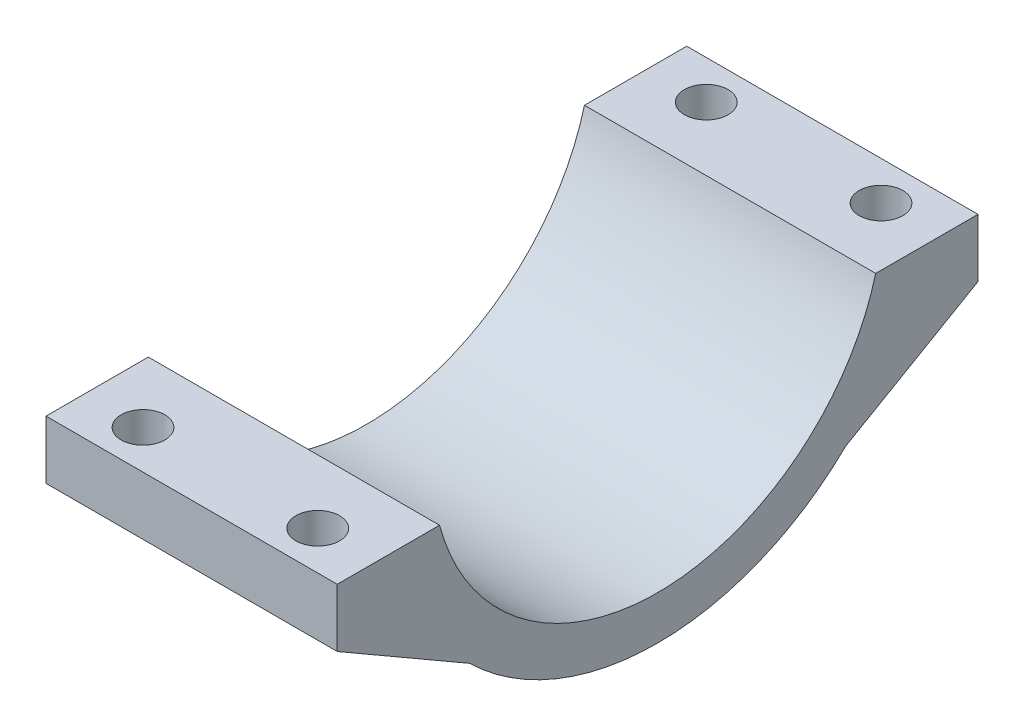
SolidWorks part; units mm, degrees
ref_plane "前视基准面" through (0, 0, 0) normal (0, 0, 1) x (1, 0, 0)
ref_plane "上视基准面" through (0, 0, 0) normal (0, 1, 0) x (1, 0, 0)
ref_plane "右视基准面" through (0, 0, 0) normal (1, 0, 0) x (0, 0, -1)
sketch "草图1" plane through (0, 0, 0) normal (1, 0, 0) x (0, 0, -1)
  line L0 (0, 0) -> (0, -4) construction
  line L1 (-22, -4) -> (-14.975, -4) construction
  line L2 (0, -4) -> (14.975, -4) construction
  line L3 (-22, -4) -> (-14.975, -4)
  line L4 (-22, -4) -> (-22, -8)
  line L5 (-22, -8) -> (-16.6808, -8)
  line L6 (22, -4) -> (22, -8)
  line L7 (14.975, -4) -> (22, -4) construction
  line L8 (0, -4) -> (14.975, -4) construction
  line L9 (14.975, -4) -> (22, -4)
  line L10 (-13.2759, -8) -> (13.2759, -8) construction
  line L11 (16.6808, -8) -> (22, -8)
  line L12 (13.2759, -8) -> (16.6808, -8) construction
  line L13 (-16.6808, -8) -> (-13.2759, -8) construction
  line L14 (-14.975, -4) -> (0, -4) construction
  line L15 (-14.975, -4) -> (0, -4) construction
  arc A0 (-14.975, -4) -> (14.975, -4) centre (0, 0) ccw
  arc A1 (-16.6808, -8) -> (16.6808, -8) centre (0, 0) ccw
  arc A2 (18.0624, -4) -> (-18.0624, -4) centre (0, 0) ccw construction
  arc A3 (14.975, -4) -> (-14.975, -4) centre (0, 0) ccw construction
  arc A4 (-18.0624, -4) -> (-16.6808, -8) centre (0, 0) ccw construction
  arc A5 (16.6808, -8) -> (18.0624, -4) centre (0, 0) ccw construction
  point P7 (0, -4)
  dimension "D1" = 31
  dimension "D4" = 37
  dimension "D2" = 44
  dimension "D3" = 4
  dimension "D5" = 4
extrude "凸台-拉伸1" add sketch "草图1" along normal blind 20
sketch "草图2" plane through (0, -8, 0) normal (0, -1, 0) x (1, 0, 0)
  line L0 (10, 22) -> (10, 16.6808) construction
  line L1 (20, 22) -> (0, 22) construction
  line L2 (20, 16.6808) -> (0, 16.6808) construction
  line L3 (0, 19.3404) -> (10, 19.3404) construction
  line L4 (0, 22) -> (0, 16.6808) construction
  circle A1 centre (4, 19.3404) radius 1.5
  circle A2 centre (16, 19.3404) radius 1.5
  dimension "D1" = 3
  dimension "D2" = 12
sketch "草图3" plane through (0, 0, 0) normal (-1, 0, 0) x (0, 0, 1)
  line L0 (22, -8) -> (12.9166, -13.2443)
  line L1 (22, -8) -> (16.6808, -8) construction
  arc A0 (-16.6808, -8) -> (16.6808, -8) centre (0, 0) ccw construction
  dimension "D1" = 30
rib "筋1" sketch "草图3" sketch "草图3" thickness 1.2 extrusion direction parallel to sketch draft on no parameters "D1"=1.2
ref_plane "基准面1" through (10, 0, 0) normal (-1, 0, 0) x (0, 0, -1)
sketch "草图4" plane through (10, 0, 0) normal (-1, 0, 0) x (0, 0, -1)
  line L0 (-22, 8) -> (-12.9166, 13.2443) construction
  line L1 (-22, 8) -> (-12.9166, 13.2443)
rib "筋2" sketch "草图4" sketch "草图4" thickness 6 extrusion direction parallel to sketch draft on no parameters "D1"=6
mirror "镜向1" about plane through (10, 0, 0) normal (-1, 0, 0) of "筋1"
ref_plane "基准面2" through (0, 0, 0) normal (0, 0, 1) x (1, 0, 0)
hole_wizard "大小mm 暗销孔1" positions "草图5" profile "草图6" hole size "Ø3.0" standard "GB"
sketch "草图5" plane through (0, -8, 0) normal (0, -1, 0) x (-1, 0, 0)
  point P0 (-16, -19.3404)
  point P3 (-4, -19.3404)
sketch "草图6" plane through (16, -8, 19.3404) normal (1, 0, 0) x (0, 0, -1)
  line L0 (0, 0) -> (0, 5.9013)
  line L1 (0, 5.9013) -> (1.5, 5)
  line L2 (1.5, 5) -> (1.5, 0)
  line L5 (1.5, 0) -> (0, 0)
  line L10 (0, 5.9013) -> (-1.5, 5) construction
  line L11 (0, -6.35) -> (0, 107.95) construction
  dimension "孔直径" = 3
  dimension "孔深度" = 5
  dimension "导头角度" = 118
mirror "镜向2" about plane through (0, 0, 0) normal (0, 0, 1) of "筋1", "镜向1", "大小mm 暗销孔1", "筋2"
